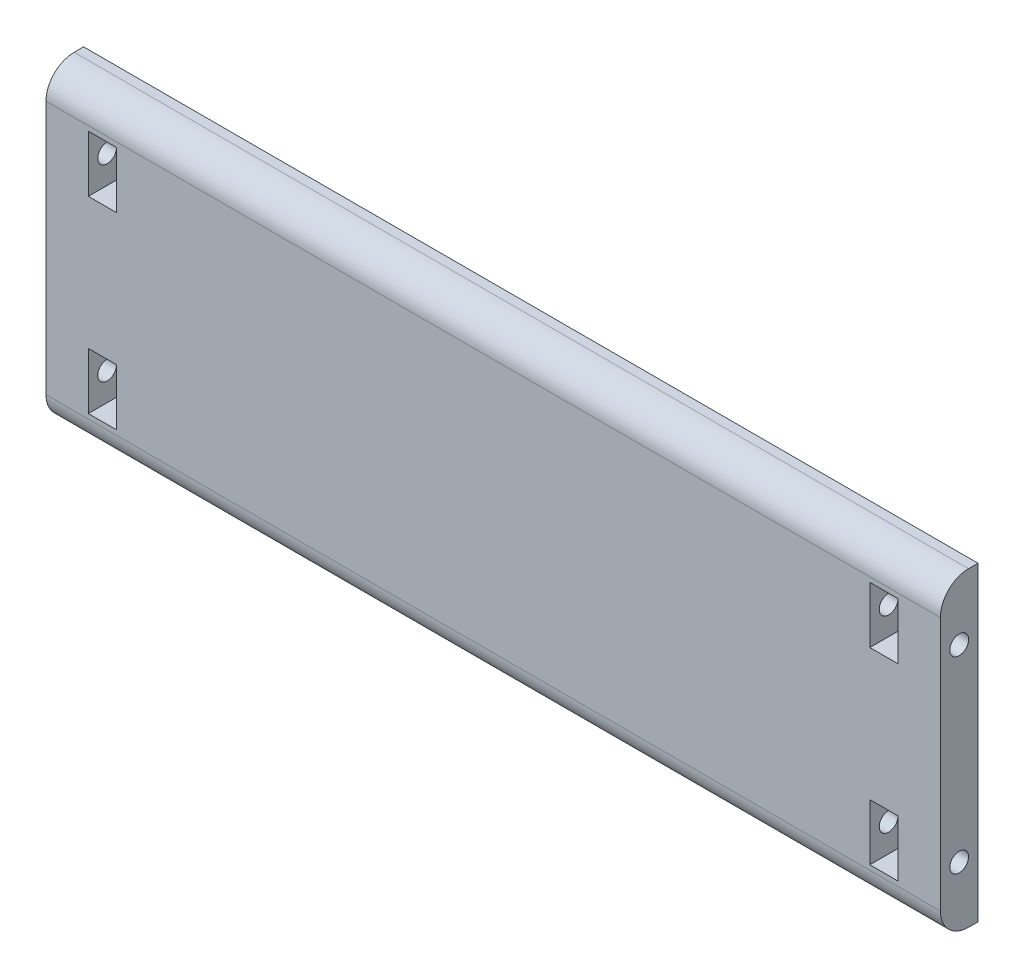
SolidWorks part; units mm, degrees
ref_plane "Plan de face" through (0, 0, 0) normal (0, 0, 1) x (1, 0, 0)
ref_plane "Plan de dessus" through (0, 0, 0) normal (0, 1, 0) x (1, 0, 0)
ref_plane "Plan de droite" through (0, 0, 0) normal (1, 0, 0) x (0, 0, -1)
sketch "Esquisse1" plane through (0, 0, 0) normal (0, 0, 1) x (1, 0, 0)
  line L0 (-41.54, 16.51) -> (-41.54, -16.51) construction
  line L1 (-47.54, 16.51) -> (47.54, 16.51)
  line L2 (-47.54, 16.51) -> (-47.54, -16.51)
  line L3 (-47.54, -16.51) -> (47.54, -16.51)
  line L4 (47.54, 16.51) -> (47.54, -16.51)
  line L5 (-47.54, 16.51) -> (47.54, -16.51) construction
  line L6 (-47.54, -16.51) -> (47.54, 16.51) construction
  line L7 (0, 16.51) -> (0, -16.51) construction
  line L8 (-43.04, -13) -> (-40.04, -13)
  line L9 (-43.04, 13) -> (-40.04, 13)
  line L10 (-43.04, 13) -> (-43.04, 7)
  line L11 (-43.04, 7) -> (-40.04, 7)
  line L12 (-40.04, 13) -> (-40.04, 7)
  line L13 (-43.04, 13) -> (-40.04, 7) construction
  line L14 (-43.04, 7) -> (-40.04, 13) construction
  line L15 (-40.04, -7) -> (-40.04, -13)
  line L16 (-43.04, -7) -> (-43.04, -13)
  line L17 (-43.04, -7) -> (-40.04, -7)
  line L18 (41.54, 16.51) -> (41.54, -16.51) construction
  line L19 (43.04, -13) -> (40.04, -13)
  line L20 (40.04, -7) -> (40.04, -13)
  line L21 (43.04, -7) -> (40.04, -7)
  line L22 (43.04, -7) -> (43.04, -13)
  line L23 (43.04, 13) -> (40.04, 13)
  line L24 (43.04, 13) -> (43.04, 7)
  line L25 (40.04, 13) -> (40.04, 7)
  line L26 (43.04, 7) -> (40.04, 7)
  line L27 (-43.04, -7) -> (-40.04, -13) construction
  line L28 (-43.04, -13) -> (-40.04, -7) construction
  point P0 (0, 0)
  point P10 (-41.54, 10)
  point P11 (-41.54, 10)
  point P30 (-41.54, -10)
  dimension "D1" = 95.08
  dimension "D2" = 33.02
  dimension "D3" = 6
  dimension "D4" = 6.51
  dimension "D5" = 6
  dimension "D6" = 3
  dimension "D7" = 2
extrude "Boss.-Extru.1" add sketch "Esquisse1" along normal blind 4
fillet "Congé1" radius 3 2 edges at (0, 16.51, 4) (0, -16.51, 4)
sketch "Esquisse4" plane through (47.54, 0, 0) normal (1, 0, 0) x (0, 0, -1)
  line L0 (-2, 16.51) -> (-2, -16.51) construction
  line L2 (-4, 13.51) -> (-4, 16.51) construction
  line L3 (-4, 16.51) -> (0, 16.51) construction
  line L4 (-1, -16.51) -> (-4, -16.51) construction
  line L5 (-4, -16.51) -> (-4, -13.51) construction
  circle A2 centre (-2, 10) radius 1
  circle A3 centre (-2, -10) radius 1
  dimension "D1" = 6.51
  dimension "D2" = 2
extrude "Enlèv. mat.-Extru.2" cut sketch "Esquisse4" against normal blind 10
sketch "Esquisse5" plane through (-47.54, 0, 0) normal (-1, 0, 0) x (0, 0, 1)
  line L0 (1, 16.51) -> (4, 16.51) construction
  line L1 (4, 16.51) -> (4, 13.51) construction
  line L2 (1, -16.51) -> (4, -16.51) construction
  line L3 (4, -16.51) -> (4, -13.51) construction
  line L4 (2, 16.51) -> (2, -16.51) construction
  circle A0 centre (2, 10) radius 1
  circle A1 centre (2, -10) radius 1
  point P8 (2, 16.51)
  dimension "D1" = 6.51
  dimension "D2" = 2
extrude "Enlèv. mat.-Extru.3" cut sketch "Esquisse5" against normal blind 10
